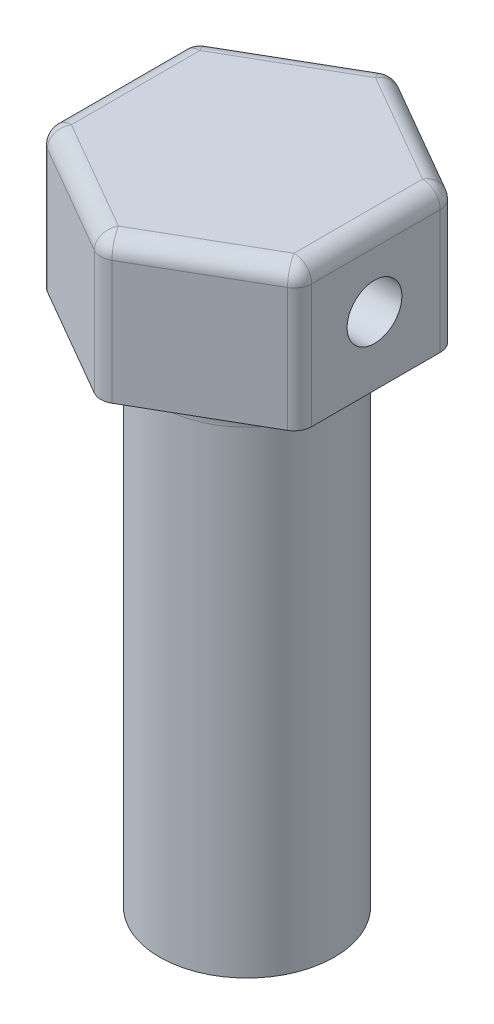
SolidWorks part; units mm, degrees
ref_plane "Front Plane" through (0, 0, 0) normal (0, 0, 1) x (1, 0, 0)
ref_plane "Top Plane" through (0, 0, 0) normal (0, 1, 0) x (1, 0, 0)
ref_plane "Right Plane" through (0, 0, 0) normal (1, 0, 0) x (0, 0, -1)
sketch "Sketch1" plane through (0, 0, 0) normal (0, 1, 0) x (1, 0, 0)
  line L1 (7.3, -4.2147) -> (7.3, 4.2147)
  line L2 (7.3, 4.2147) -> (0, 8.4293)
  line L3 (0, 8.4293) -> (-7.3, 4.2147)
  line L4 (-7.3, 4.2147) -> (-7.3, -4.2147)
  line L5 (-7.3, -4.2147) -> (0, -8.4293)
  line L6 (0, -8.4293) -> (7.3, -4.2147)
  circle A0 centre (0, 0) radius 7.3 construction
  dimension "D1" = 14.6
extrude "Boss-Extrude1" add sketch "Sketch1" along normal blind 8
sketch "Sketch2" plane through (0, 0, 0) normal (0, -1, 0) x (1, 0, 0)
  line L0 (-1.5, 1.4518) -> (-1.5, -1.4518)
  line L1 (-7.3, -4.2147) -> (-7.3, 4.2147) construction
  arc A0 (-1.5, -1.4518) -> (-1.5, 1.4518) centre (0, 0) ccw
  circle A1 centre (0, 0) radius 4.95
  dimension "D1" = 4.175
  dimension "D2" = 9.9
  dimension "D3" = 1.5
extrude "Boss-Extrude2" add sketch "Sketch2" along normal blind 29 contours A1 | A0 L0
fillet "Fillet1" radius 2 1 edges at (0, 0, 4.95)
sketch "Sketch3" plane through (7.3, 0, 0) normal (1, 0, 0) x (0, 0, -1)
  line L0 (-6.95, 0) -> (6.95, 0) construction
  line L1 (4.2147, 8) -> (4.2147, 0) construction
  circle A0 centre (-0.0853, 3.85) radius 1.55
  dimension "D1" = 3.1
  dimension "D2" = 3.85
  dimension "D3" = 4.3
extrude "Cut-Extrude1" cut sketch "Sketch3" against normal through all
fillet "Fillet2" radius 1 12 edges at (-3.65, 8, 6.322) (-7.3, 8, 0) (-3.65, 8, -6.322) (3.65, 8, -6.322) (7.3, 8, 0) (3.65, 8, 6.322) (-7.3, 4, -4.2147) (0, 4, -8.4293) (7.3, 4, -4.2147) (7.3, 4, 4.2147) (0, 4, 8.4293) (-7.3, 4, 4.2147)
sketch "Sketch4" plane through (0, 0, 0) normal (1, 0, 0) x (0, 0, -1)
  line L1 (-16.1086, 1.5942) -> (18.1695, 1.5942)
  line L2 (-16.1086, 1.5942) -> (-16.1086, -34.824)
  line L3 (-16.1086, -34.824) -> (18.1695, -34.824)
  line L4 (18.1695, 1.5942) -> (18.1695, -34.824)
extrude "Cut-Extrude2" [suppressed] cut sketch "Sketch4" against normal through all both and the other way through all
sketch "Sketch5" plane through (0, -29, 0) normal (0, -1, 0) x (1, 0, 0)
  circle A0 centre (0, 0) radius 2.0875
  dimension "D1" = 4.175
extrude "Cut-Extrude3" cut sketch "Sketch5" against normal blind 2
